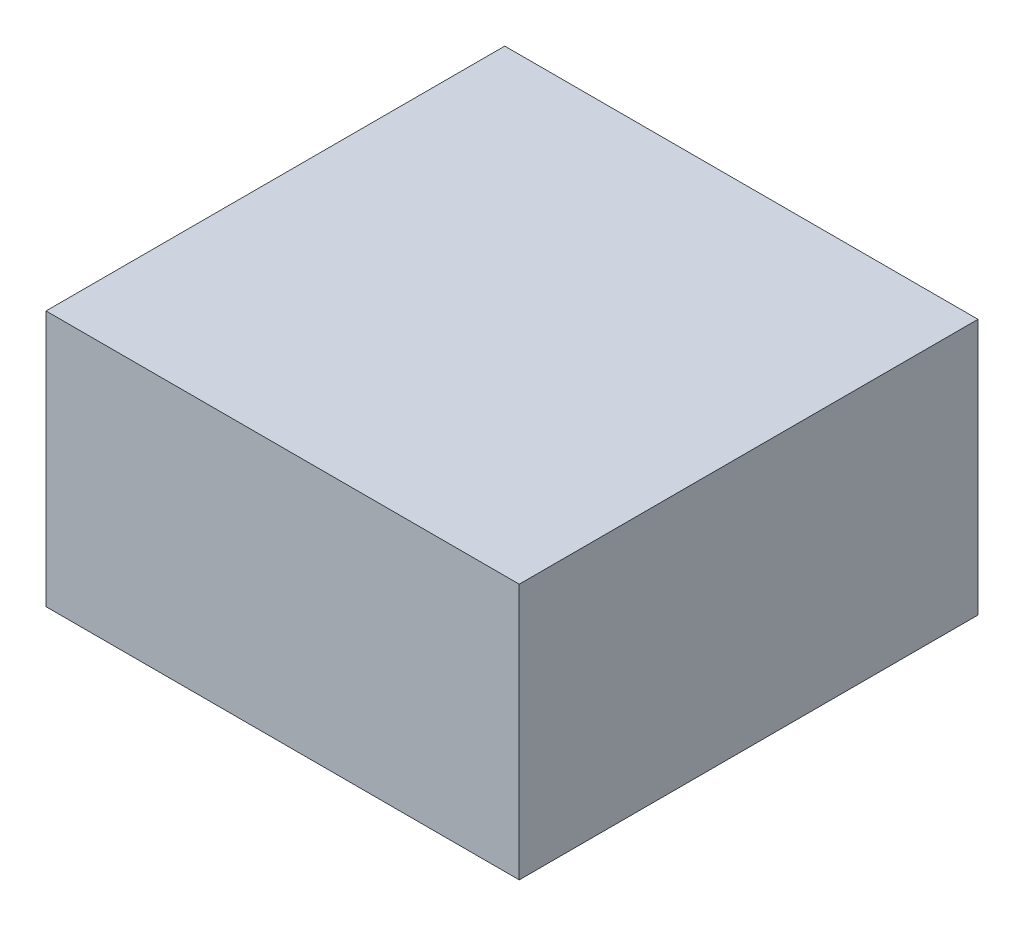
SolidWorks part; units mm, degrees
ref_plane "Front Plane" through (0, 0, 0) normal (0, 0, 1) x (1, 0, 0)
ref_plane "Top Plane" through (0, 0, 0) normal (0, 1, 0) x (1, 0, 0)
ref_plane "Right Plane" through (0, 0, 0) normal (1, 0, 0) x (0, 0, -1)
sketch "Sketch1" plane through (0, 0, 0) normal (0, 1, 0) x (1, 0, 0)
  line L1 (0, 0) -> (18.477, 0)
  line L2 (0, 0) -> (0, 17.9114)
  line L3 (0, 17.9114) -> (18.477, 17.9114)
  line L4 (18.477, 0) -> (18.477, 17.9114)
extrude "Boss-Extrude1" add sketch "Sketch1" along normal blind 10
